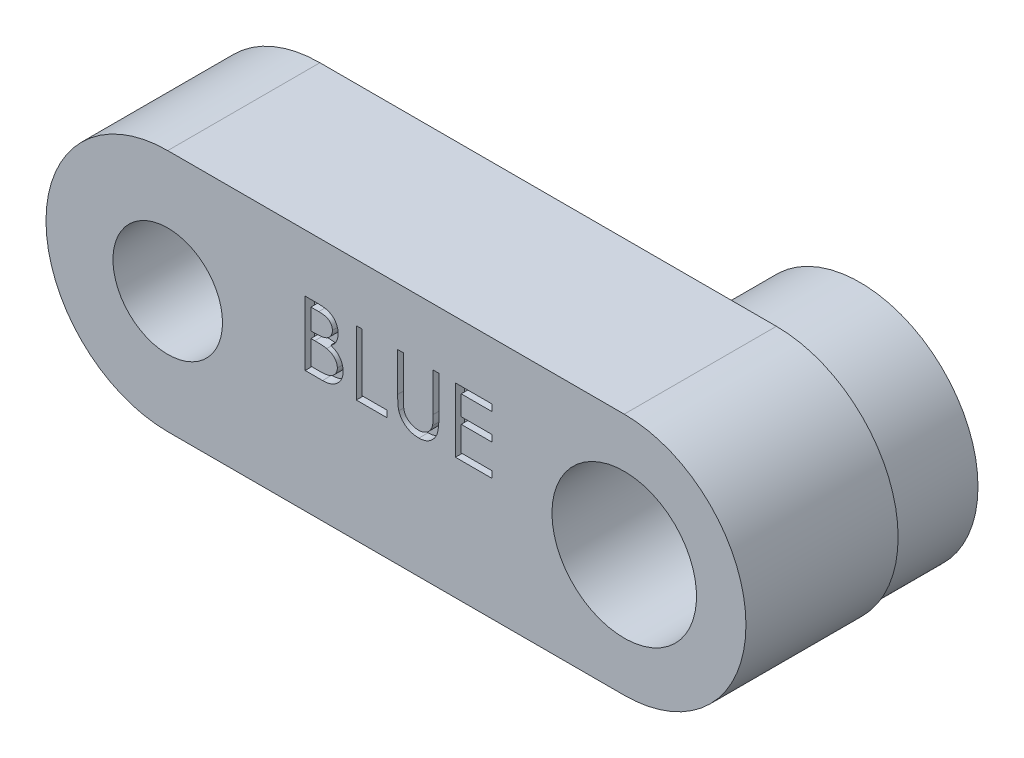
SolidWorks part; units mm, degrees
ref_plane "Front Plane" through (0, 0, 0) normal (0, 0, 1) x (1, 0, 0)
ref_plane "Top Plane" through (0, 0, 0) normal (0, 1, 0) x (1, 0, 0)
ref_plane "Right Plane" through (0, 0, 0) normal (1, 0, 0) x (0, 0, -1)
sketch "Sketch1" plane through (0, 0, 0) normal (0, 0, 1) x (1, 0, 0)
  line L0 (-7.5, 0) -> (7.5, 0) construction
  line L1 (-7.5, 4) -> (7.5, 4)
  line L2 (-7.5, -4) -> (7.5, -4)
  arc A0 (-7.5, 4) -> (-7.5, -4) centre (-7.5, 0) ccw
  arc A1 (7.5, -4) -> (7.5, 4) centre (7.5, 0) ccw
  circle A2 centre (-7.5, 0) radius 1.8
  circle A3 centre (7.5, 0) radius 1.45
  point P3 (0, 0)
extrude "Boss-Extrude1" add sketch "Sketch1" along normal mid plane 5
sketch "Sketch2" [suppressed] plane through (0, 0, 1) normal (0, 0, 1) x (1, 0, 0)
  line L0 (-25, 0) -> (25, 0) construction
  text T0 "RED" font "Century Gothic" height in points 8
extrude "Cut-Extrude1" [suppressed] cut sketch "Sketch2" against normal blind 0.3
sketch "Sketch3" plane through (0, 0, 2.5) normal (0, 0, 1) x (1, 0, 0)
  line L0 (-7.5, 0) -> (7.5, 0) construction
  text T0 "BLUE" font "Century Gothic" height in points 8
extrude "Cut-Extrude2" cut sketch "Sketch3" against normal blind 0.3
sketch "Sketch4" [suppressed] plane through (0, 0, 2.5) normal (0, 0, 1) x (1, 0, 0)
  line L0 (-25, 0) -> (25, 0) construction
  text T0 "GREEN" font "Century Gothic" height in points 8
extrude "Cut-Extrude3" [suppressed] cut sketch "Sketch4" against normal blind 0.3
sketch "Sketch5" [suppressed] plane through (0, 0, 2.5) normal (0, 0, 1) x (1, 0, 0)
  line L0 (-20.75, 0) -> (20.75, 0) construction
  text T0 "RED" font "Century Gothic" height in points 8
extrude "Cut-Extrude4" [suppressed] cut sketch "Sketch5" against normal blind 0.3
sketch "Sketch6" [suppressed] plane through (0, 0, 2.5) normal (0, 0, 1) x (1, 0, 0)
  line L0 (-20.05, 0) -> (20.05, 0) construction
  text T0 "RED" font "Century Gothic" height in points 8
extrude "Cut-Extrude5" [suppressed] cut sketch "Sketch6" against normal blind 0.3
sketch "Sketch7" [suppressed] plane through (0, 0, 2.5) normal (0, 0, 1) x (1, 0, 0)
  line L0 (-19.7, 0) -> (19.7, 0) construction
  text T0 "PURPLE" font "Century Gothic" height in points 8
extrude "Cut-Extrude6" [suppressed] cut sketch "Sketch7" against normal blind 0.3
sketch "Sketch8" [suppressed] plane through (0, 0, 2.5) normal (0, 0, 1) x (1, 0, 0)
  line L0 (-30.95, 0) -> (0, 0) construction
  text T0 "ORANGE" font "Century Gothic" height in points 8
extrude "Cut-Extrude7" [suppressed] cut sketch "Sketch8" against normal blind 0.3
sketch "Sketch9" [suppressed] plane through (0, 0, 2.5) normal (0, 0, 1) x (1, 0, 0)
  line L0 (-19.65, 0) -> (19.65, 0) construction
  text T0 "MOSS" font "Century Gothic" height in points 8
sketch "Sketch10" [suppressed] plane through (0, 0, 2.5) normal (0, 0, 1) x (1, 0, 0)
  line L0 (-18.35, 0) -> (18.35, 0) construction
  text T0 "BLUE" font "Century Gothic" height in points 8
sketch "Sketch11" [suppressed] plane through (0, 0, 2.5) normal (0, 0, 1) x (1, 0, 0)
  line L0 (-24.5, 0) -> (24.5, 0) construction
sketch "Sketch12" [suppressed] plane through (0, 0, 2.5) normal (0, 0, 1) x (1, 0, 0)
  text T0 "BLUE" font "Century Gothic" height in points 8
extrude "Cut-Extrude8" [suppressed] cut sketch "Sketch12" against normal blind 0.3
sketch "Sketch13" [suppressed] plane through (0, 0, 2.5) normal (0, 0, 1) x (1, 0, 0)
  line L0 (-32.85, 0) -> (32.85, 0) construction
  text T0 "BLUE" font "Century Gothic" height in points 8
extrude "Cut-Extrude9" [suppressed] cut sketch "Sketch13" against normal blind 0.3
extrude "Cut-Extrude10" [suppressed] cut sketch "Sketch10" against normal blind 0.3
extrude "Cut-Extrude11" [suppressed] cut sketch "Sketch9" against normal blind 0.3
sketch "Sketch14" plane through (0, 0, -2.5) normal (0, 0, -1) x (-1, 0, 0)
  circle A0 centre (-7.5, 0) radius 2.375
  circle A1 centre (-7.5, 0) radius 1.45 construction
  dimension "D1" = 4.75
extrude "Cut-Extrude12" cut sketch "Sketch14" against normal through all
sketch "Sketch16" plane through (0, 0, 2.5) normal (0, 0, 1) x (1, 0, 0)
  line L0 (7.5, 4) -> (-7.5, 4) construction
  line L2 (-11.5, 4) -> (-19.3257, 4)
  line L3 (-11.5, 4) -> (-11.5, 2.5)
  line L4 (-11.5, 2.5) -> (-19.3257, 2.5)
  line L5 (-19.3257, 4) -> (-19.3257, 2.5)
  dimension "D1" = 19
  dimension "D2" = 26.8257
  dimension "D3" = 1.5
extrude "Cut-Extrude13" [suppressed] cut sketch "Sketch16" against normal through all
sketch "Sketch17" plane through (0, 0, -2.5) normal (0, 0, -1) x (-1, 0, 0)
  circle A0 centre (-7.5, 0) radius 2.375 construction
  circle A1 centre (-7.5, 0) radius 2.375
  circle A2 centre (-7.5, 0) radius 3.875
  dimension "D1" = 1.5
extrude "Boss-Extrude2" add sketch "Sketch17" along normal blind 2.75
ref_plane "Plane1" through (0, 0, -3.25) normal (0, 0, -1) x (-1, 0, 0)
sketch "Sketch18" plane through (0, 0, -3.25) normal (0, 0, -1) x (-1, 0, 0)
  circle A1 centre (-7.5, 0) radius 2.375 construction
  circle A2 centre (-7.5, 0) radius 1.375
  circle A3 centre (-7.5, 0) radius 1.375
  circle A4 centre (-7.5, 0) radius 2.375
  dimension "D1" = 1
extrude "Boss-Extrude3" add sketch "Sketch18" against normal blind 0.8
equation "\"Scale\"= 1"
